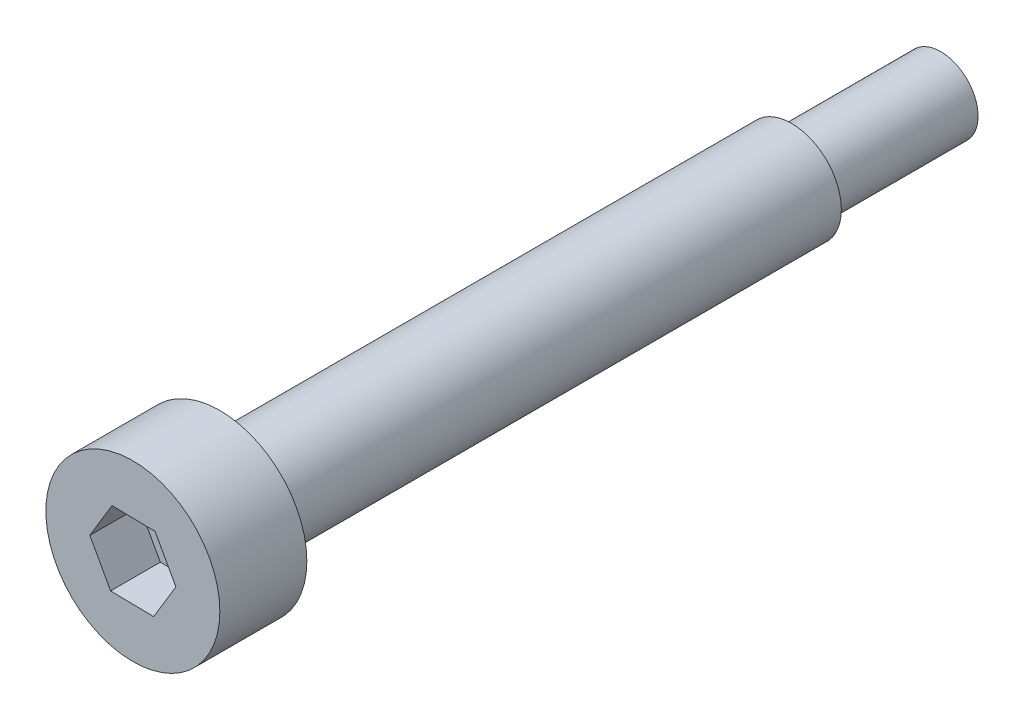
SolidWorks part; units mm, degrees
material "AISI 304"
ref_plane "前视基准面" through (0, 0, 0) normal (0, 0, 1) x (1, 0, 0)
ref_plane "上视基准面" through (0, 0, 0) normal (0, 1, 0) x (1, 0, 0)
ref_plane "右视基准面" through (0, 0, 0) normal (1, 0, 0) x (0, 0, -1)
sketch "草图1" plane through (0, 0, 0) normal (0, 0, 1) x (1, 0, 0)
  circle A0 centre (0, 0) radius 3.5
  dimension "D1" = 7
extrude "凸台-拉伸1" add sketch "草图1" along normal blind 3.5
sketch "草图2" plane through (0, 0, 3.5) normal (0, 0, 1) x (1, 0, 0)
  line L1 (0.8936, 1.4837) -> (-0.8381, 1.5158)
  line L2 (-0.8381, 1.5158) -> (-1.7318, 0.0321)
  line L3 (-1.7318, 0.0321) -> (-0.8936, -1.4837)
  line L4 (-0.8936, -1.4837) -> (0.8381, -1.5158)
  line L5 (0.8381, -1.5158) -> (1.7318, -0.0321)
  line L6 (1.7318, -0.0321) -> (0.8936, 1.4837)
  circle A0 centre (0, 0) radius 1.5 construction
  dimension "D1" = 3
extrude "切除-拉伸1" cut sketch "草图2" against normal blind 2
sketch "草图3" plane through (0, 0, 0) normal (0, 0, -1) x (-1, 0, 0)
  circle A0 centre (0, 0) radius 2
  dimension "D1" = 4
extrude "凸台-拉伸2" add sketch "草图3" along normal blind 23
sketch "草图4" plane through (0, 0, -23) normal (0, 0, -1) x (-1, 0, 0)
  circle A0 centre (0, 0) radius 1.5
  dimension "D1" = 3
extrude "凸台-拉伸3" add sketch "草图4" along normal blind 6
cosmetic thread "装饰螺纹线1" parameters "D2"=2
